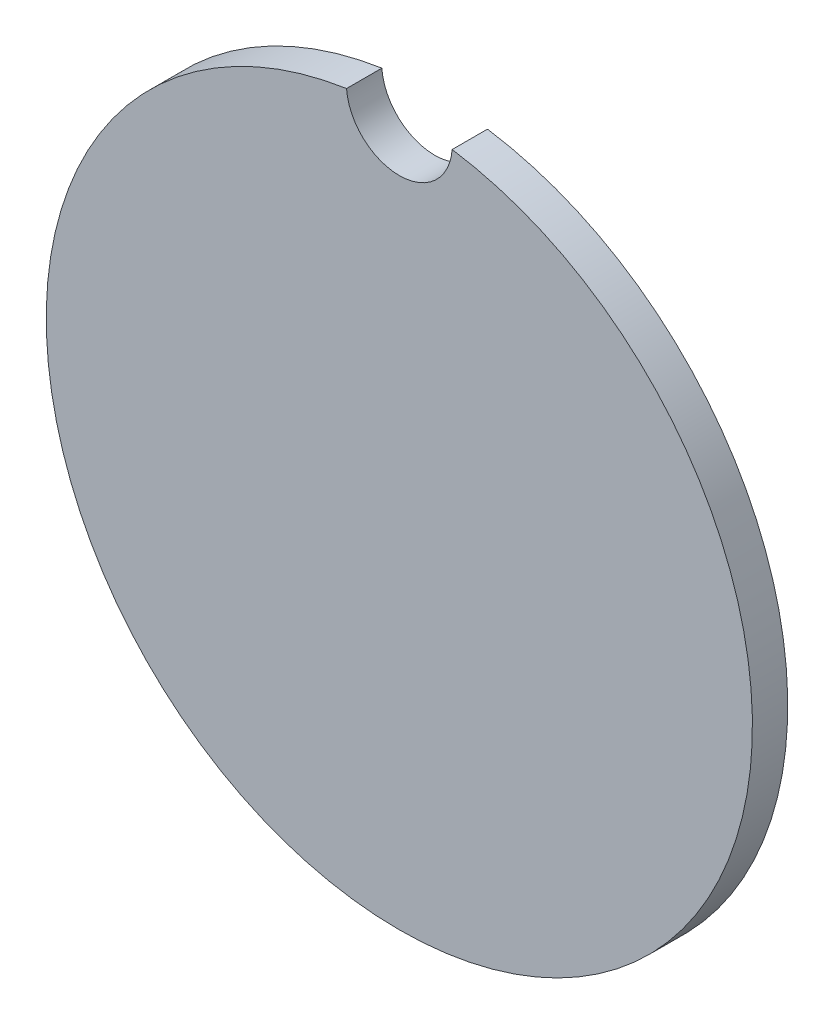
SolidWorks part; units mm, degrees
ref_plane "Front Plane" through (0, 0, 0) normal (0, 0, 1) x (1, 0, 0)
ref_plane "Top Plane" through (0, 0, 0) normal (0, 1, 0) x (1, 0, 0)
ref_plane "Right Plane" through (0, 0, 0) normal (1, 0, 0) x (0, 0, -1)
sketch "Sketch1" plane through (0, 0, 0) normal (0, 0, 1) x (1, 0, 0)
  arc A0 (-0.7479, 4.9438) -> (0.7479, 4.9438) centre (0, 0) ccw
  arc A1 (-0.7479, 4.9438) -> (0.7479, 4.9438) centre (0, 5) ccw
  dimension "D1" = 10
  dimension "D2" = 1.5
extrude "Boss-Extrude1" add sketch "Sketch1" along normal blind 0.5
sketch "Sketch2" plane through (0, 0, 0.5) normal (0, 0, 1) x (1, 0, 0)
  line L0 (0, 0) -> (0, -5) construction
  arc A0 (-0.7479, 4.9438) -> (0.7479, 4.9438) centre (0, 0) ccw construction
